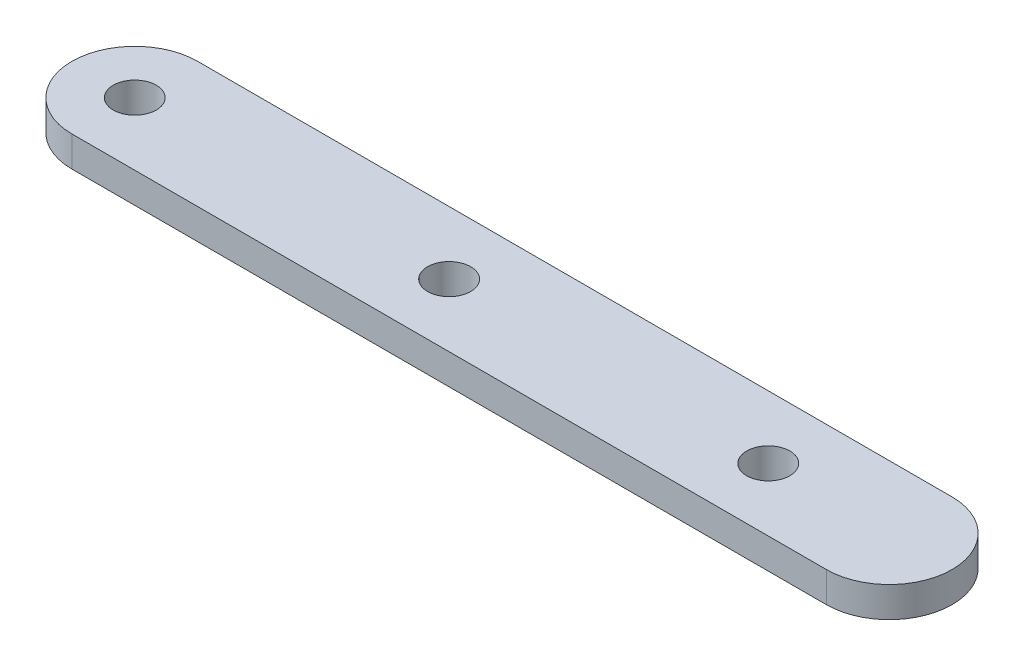
SolidWorks part; units mm, degrees
material "PET"
ref_plane "Front" through (0, 0, 0) normal (0, 0, 1) x (1, 0, 0)
ref_plane "Top" through (0, 0, 0) normal (0, 1, 0) x (1, 0, 0)
ref_plane "Right" through (0, 0, 0) normal (1, 0, 0) x (0, 0, -1)
sketch "Sketch1" plane through (0, 0, 0) normal (0, 1, 0) x (1, 0, 0)
  line L1 (-62.8447, 8.7002) -> (13.3553, 8.7002)
  line L3 (-62.8447, -3.9998) -> (13.3553, -3.9998)
  line L5 (-62.8447, 8.7002) -> (13.3553, -3.9998) construction
  line L6 (-62.8447, -3.9998) -> (13.3553, 8.7002) construction
  arc A0 (-62.8447, 8.7002) -> (-62.8447, -3.9998) centre (-62.8447, 2.3502) ccw
  arc A2 (13.3553, 8.7002) -> (13.3553, -3.9998) centre (13.3553, 2.3502) cw
  point P4 (-24.7447, 2.3502)
  dimension "D1" = 76.2
  dimension "D2" = 12.7
extrude "Boss-Extrude1" add sketch "Sketch1" along normal blind 3.075
sketch "Sketch2" plane through (0, 3.075, 0) normal (0, 1, 0) x (1, 0, 0)
  circle A0 centre (-62.8447, 2.3502) radius 2.175
  circle A1 centre (-31.0947, 2.3502) radius 2.175
  circle A2 centre (1.1353, 2.3502) radius 2.175
  arc A3 (13.3553, -3.9998) -> (13.3553, 8.7002) centre (13.3553, 2.3502) ccw construction
  dimension "D1" = 31.75
  dimension "D2" = 4.35
  dimension "D3" = 4.35
  dimension "D4" = 4.35
  dimension "D5" = 12.22
extrude "Cut-Extrude2" cut sketch "Sketch2" against normal blind 6.35
